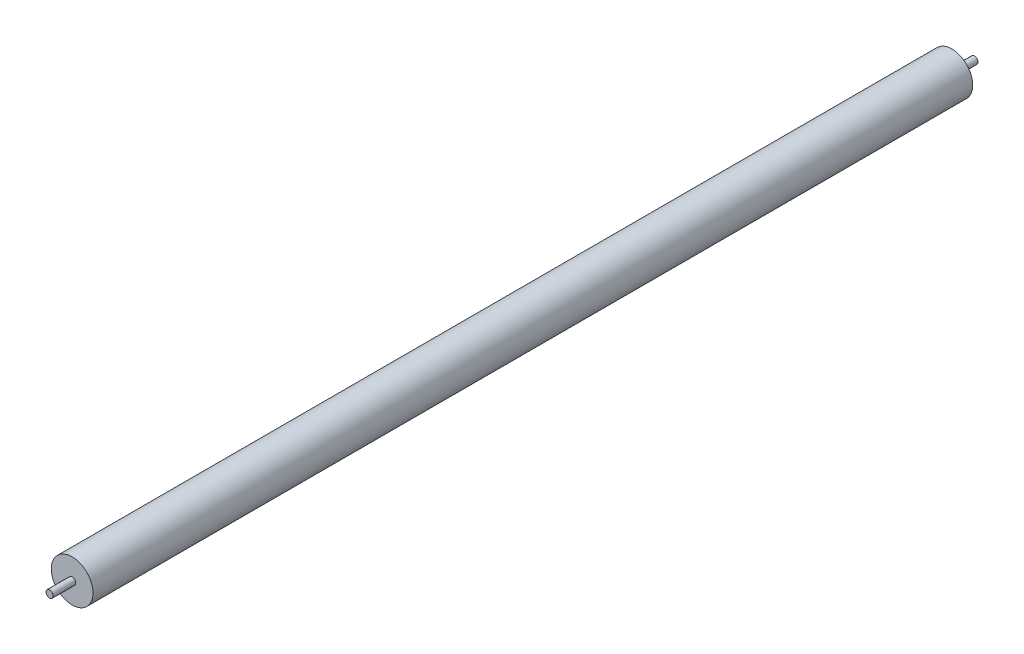
SolidWorks part; units mm, degrees
ref_plane "Alzado" through (0, 0, 0) normal (0, 0, 1) x (1, 0, 0)
ref_plane "Planta" through (0, 0, 0) normal (0, 1, 0) x (1, 0, 0)
ref_plane "Vista lateral" through (0, 0, 0) normal (1, 0, 0) x (0, 0, -1)
sketch "Sketch1" plane through (0, 0, 0) normal (0, 0, 1) x (1, 0, 0)
  circle A0 centre (0, 0) radius 18.5
  dimension "D1" = 37
extrude "Boss-Extrude1" add sketch "Sketch1" along normal mid plane 780
sketch "Sketch2" plane through (0, 0, 0) normal (0, 0, 1) x (1, 0, 0)
  circle A0 centre (0, 0) radius 3.175
  dimension "D1" = 6.35
extrude "Boss-Extrude2" add sketch "Sketch2" along normal mid plane 820
